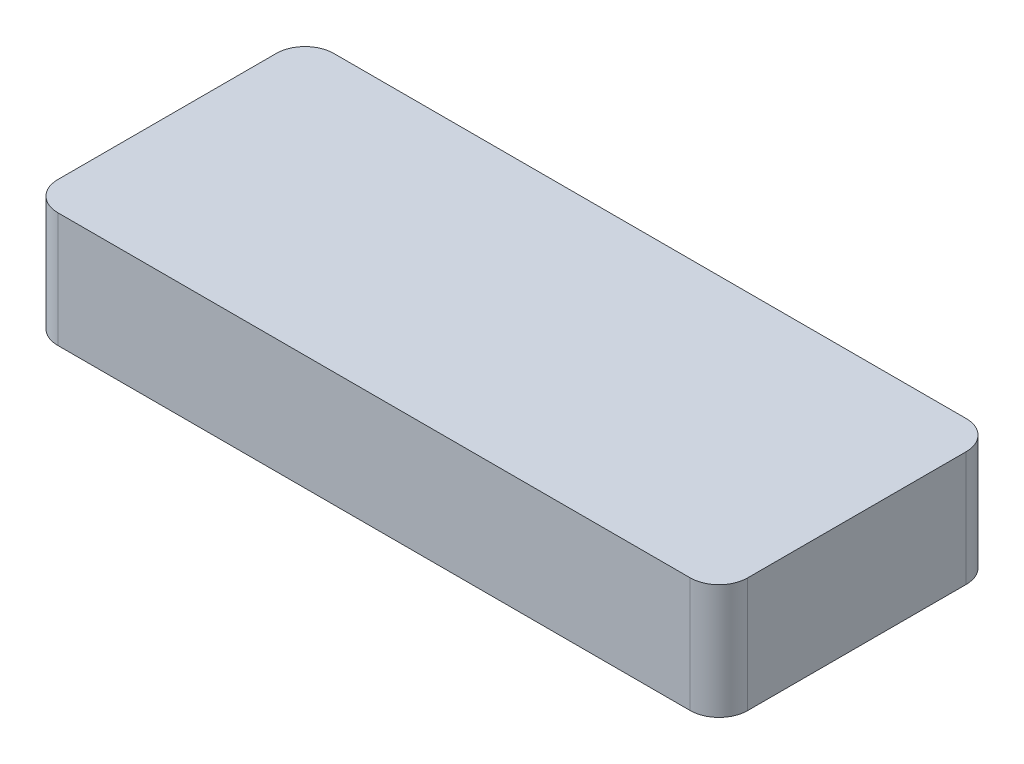
SolidWorks part; units mm, degrees
ref_plane "Front Plane" through (0, 0, 0) normal (0, 0, 1) x (1, 0, 0)
ref_plane "Top Plane" through (0, 0, 0) normal (0, 1, 0) x (1, 0, 0)
ref_plane "Right Plane" through (0, 0, 0) normal (1, 0, 0) x (0, 0, -1)
sketch "Sketch1" plane through (0, 0, 0) normal (0, 1, 0) x (1, 0, 0)
  line L0 (0, 0) -> (0, 6.096)
  line L1 (0, -54.9123) -> (0, 54.9123) construction
  line L2 (0, 6.096) -> (15.24, 6.096)
  line L3 (15.24, 6.096) -> (15.24, 0)
  line L4 (-55, 0) -> (55, 0) construction
  line L5 (15.24, 0) -> (0, 0)
  dimension "D1" = 15.24
  dimension "D2" = 6.096
extrude "Boss-Extrude1" add sketch "Sketch1" along normal blind 2.54 contours L2 L3 L5 L0
shell "Shell1" thickness 0.635
fillet "Fillet1" radius 0.635 4 edges at (15.24, 1.27, -6.096) (15.24, 1.27, 0) (0, 1.27, -6.096) (0, 1.27, 0)
sketch "Sketch2" plane through (0, 1.905, 0) normal (0, -1, 0) x (1, 0, 0)
  line L0 (14.605, -0.635) -> (0.635, -0.635) construction
  line L2 (7.62, -0.635) -> (7.62, -5.461) construction
  line L3 (0.635, -5.461) -> (14.605, -5.461) construction
  line L4 (0.635, -3.048) -> (14.605, -3.048) construction
  line L5 (0.635, -0.635) -> (0.635, -5.461) construction
  line L6 (14.605, -5.461) -> (14.605, -0.635) construction
  circle A0 centre (7.62, -3.048) radius 1.5875
  dimension "D1" = 3.175
extrude "Boss-Extrude2" add sketch "Sketch2" along normal up to surface (1.905 mm away) up to face at (7.62, 0, -3.048)
